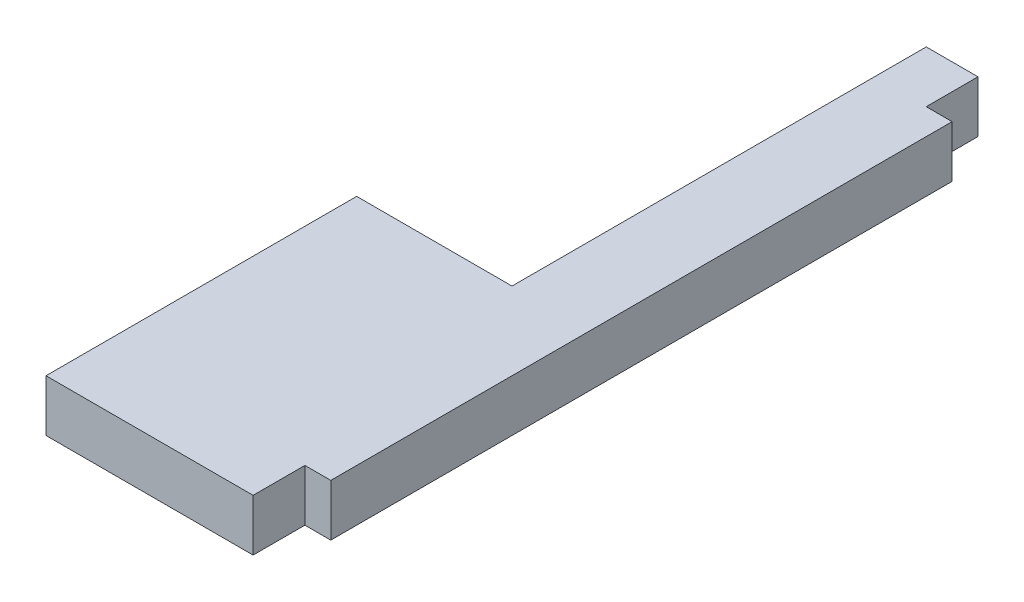
SolidWorks part; units mm, degrees
ref_plane "Front Plane" through (0, 0, 0) normal (0, 0, 1) x (1, 0, 0)
ref_plane "Top Plane" through (0, 0, 0) normal (0, 1, 0) x (1, 0, 0)
ref_plane "Right Plane" through (0, 0, 0) normal (1, 0, 0) x (0, 0, -1)
sketch "Sketch2" plane through (0, 0, 0) normal (0, 1, 0) x (1, 0, 0)
  line L0 (0, 0) -> (40, 0)
  line L1 (40, 0) -> (40, 10)
  line L2 (40, 10) -> (45, 10)
  line L3 (0, 0) -> (0, 60)
  line L4 (45, 10) -> (45, 130)
  line L5 (45, 130) -> (40, 130)
  line L6 (40, 130) -> (40, 140)
  line L7 (40, 140) -> (30, 140)
  line L8 (30, 140) -> (30, 60)
  line L9 (30, 60) -> (0, 60)
extrude "Boss-Extrude1" add sketch "Sketch2" along normal blind 10
